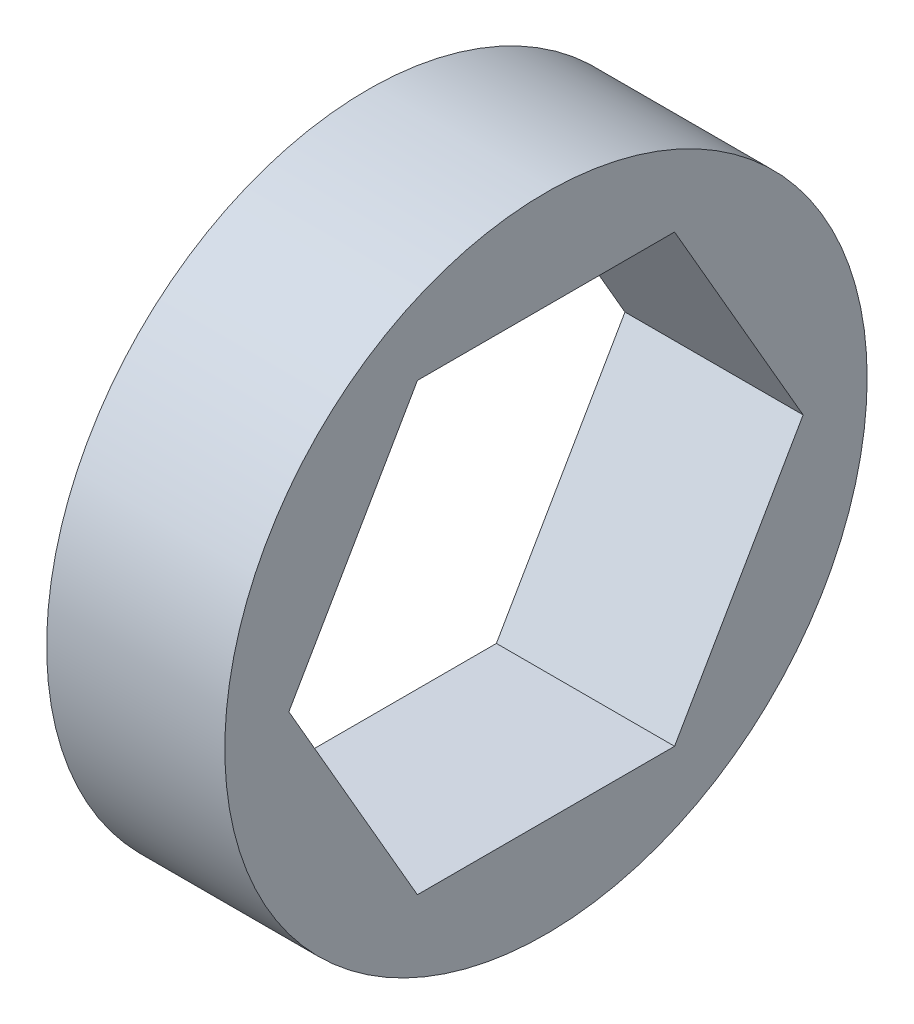
SolidWorks part; units mm, degrees
ref_plane "Front Plane" through (0, 0, 0) normal (0, 0, 1) x (1, 0, 0)
ref_plane "Top Plane" through (0, 0, 0) normal (0, 1, 0) x (1, 0, 0)
ref_plane "Right Plane" through (0, 0, 0) normal (1, 0, 0) x (0, 0, -1)
sketch "Sketch1" plane through (0, 0, 0) normal (1, 0, 0) x (0, 0, -1)
  line L1 (7.6256, 0) -> (3.8128, 6.604)
  line L2 (3.8128, 6.604) -> (-3.8128, 6.604)
  line L3 (-3.8128, 6.604) -> (-7.6256, 0)
  line L4 (-7.6256, 0) -> (-3.8128, -6.604)
  line L5 (-3.8128, -6.604) -> (3.8128, -6.604)
  line L6 (3.8128, -6.604) -> (7.6256, 0)
  circle A1 centre (0, 0) radius 9.525
  circle A2 centre (0, 0) radius 6.604 construction
  dimension "D1" = 19.05
  dimension "D2" = 13.208
extrude "Boss-Extrude1" add sketch "Sketch1" along normal blind 5.2832
